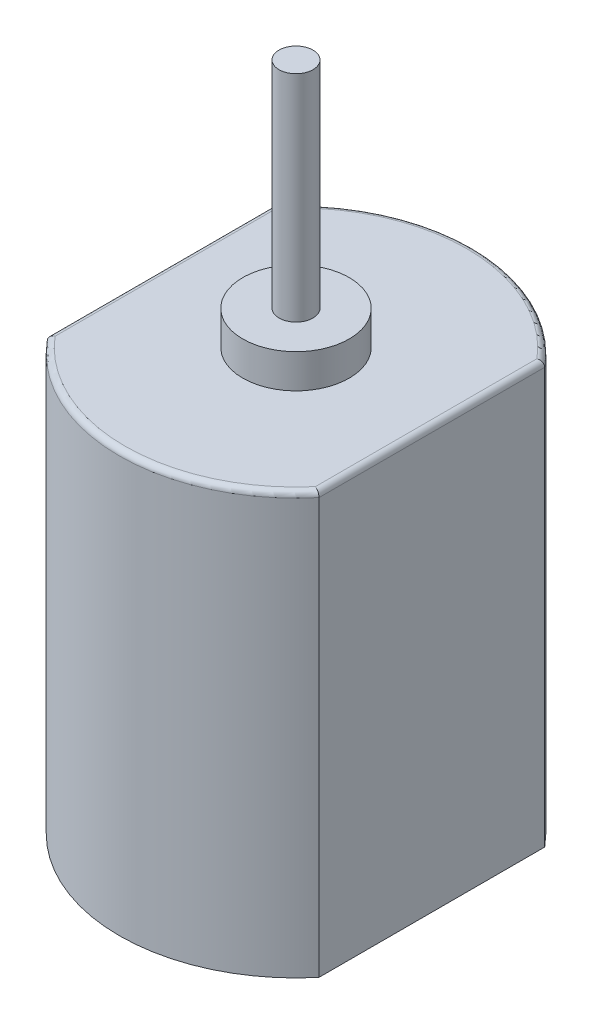
SolidWorks part; units mm, degrees
ref_plane "Front Plane" through (0, 0, 0) normal (0, 0, 1) x (1, 0, 0)
ref_plane "Top Plane" through (0, 0, 0) normal (0, 1, 0) x (1, 0, 0)
ref_plane "Right Plane" through (0, 0, 0) normal (1, 0, 0) x (0, 0, -1)
sketch "Sketch1" plane through (0, 0, 0) normal (0, 1, 0) x (1, 0, 0)
  line L0 (-6, 4.984) -> (-6, -4.984)
  line L1 (6, 4.984) -> (6, -4.984)
  arc A0 (-6, -4.984) -> (6, -4.984) centre (0, 0) ccw
  arc A1 (6, 4.984) -> (-6, 4.984) centre (0, 0) ccw
  dimension "D1" = 15.6
  dimension "D2" = 12
extrude "Boss-Extrude1" add sketch "Sketch1" along normal blind 18.6
sketch "Sketch2" plane through (0, 0, 0) normal (0, -1, 0) x (1, 0, 0)
  line L5 (-1.602, 3.7741) -> (1.602, -3.7741)
  line L7 (6, 4.984) -> (6, -4.984) construction
  line L8 (-1.2129, 4.2651) -> (-1.0957, 3.989)
  line L9 (-1.0957, 3.989) -> (0.285, 4.5751)
  line L10 (0.285, 4.5751) -> (0.1678, 4.8512)
  line L11 (0.1678, 4.8512) -> (-1.2129, 4.2651)
  line L12 (-0.285, -4.5751) -> (-0.1678, -4.8512)
  line L13 (-0.1678, -4.8512) -> (1.2129, -4.2651)
  line L14 (1.2129, -4.2651) -> (1.0957, -3.989)
  line L15 (1.0957, -3.989) -> (-0.285, -4.5751)
  point P6 (-0.5226, 4.5582)
  point P15 (0.5226, -4.5582)
  dimension "D1" = 23
  dimension "D2" = 1.3
  dimension "D3" = 1.5
  dimension "D4" = 0.3
  dimension "D5" = 1.3
  dimension "D6" = 0.3
  dimension "D7" = 1.5
  dimension "D8" = 8.2
extrude "Boss-Extrude2" add sketch "Sketch2" along normal blind 2.2 contours L14 L15 L12 L13 | L10 L11 L8 L9
sketch "Sketch3" plane through (0, 18.6, 0) normal (0, 1, 0) x (1, 0, 0)
  circle A0 centre (0, 0) radius 2.35
  dimension "D1" = 4.7
extrude "Boss-Extrude3" add sketch "Sketch3" along normal blind 1.5 contours A0
sketch "Sketch4" plane through (0, 20.1, 0) normal (0, 1, 0) x (1, 0, 0)
  circle A0 centre (0, 0) radius 0.75
  dimension "D1" = 1.5
extrude "Boss-Extrude4" add sketch "Sketch4" along normal blind 9.5 contours A0
fillet "Fillet2" radius 0.25 4 edges at (0, 18.6, 7.8) (-6, 18.6, 0) (6, 18.6, 0) (0, 18.6, -7.8)
